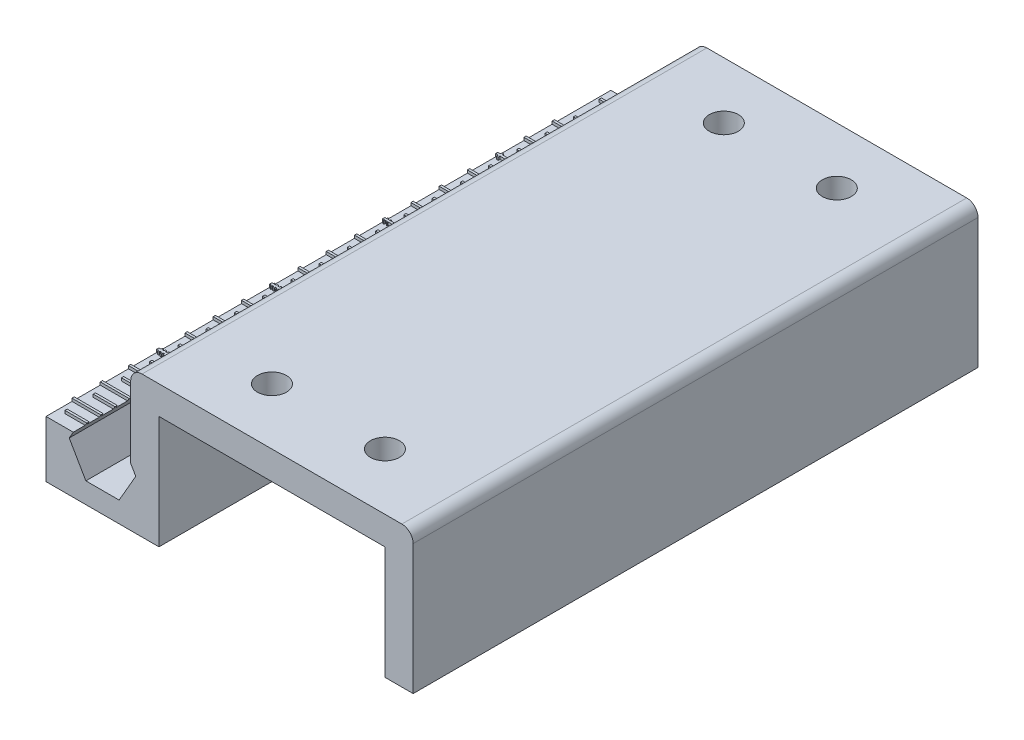
SolidWorks part; units mm, degrees
material "Printed PLA Orthotropic"
ref_plane "Front Plane" through (0, 0, 0) normal (0, 0, 1) x (1, 0, 0)
ref_plane "Top Plane" through (0, 0, 0) normal (0, 1, 0) x (1, 0, 0)
ref_plane "Right Plane" through (0, 0, 0) normal (1, 0, 0) x (0, 0, -1)
sketch "Sketch1" plane through (0, 0, 0) normal (0, 0, 1) x (1, 0, 0)
  line L0 (50.8, 0) -> (57.15, 0)
  line L2 (0, 0) -> (0, 25.4)
  line L3 (0, 25.4) -> (50.8, 25.4)
  line L4 (50.8, 0) -> (50.8, 25.4)
  line L5 (57.15, 0) -> (57.15, 29.21)
  line L6 (54.61, 31.75) -> (-3.81, 31.75)
  line L7 (0, 0) -> (-25.4, 0)
  line L14 (-25.4, 0) -> (-25.4, 12.7)
  line L15 (-6.35, 29.21) -> (-6.35, 13.068)
  line L16 (-25.4, 12.7) -> (-19.2625, 12.7)
  line L17 (-7.0908, 14.351) -> (-8.9605, 17.5895) construction
  line L18 (-12.7, 17.5895) -> (-16.4395, 17.5895) construction
  line L19 (-19.2625, 12.7) -> (-20.179, 11.1125)
  line L20 (-20.179, 11.1125) -> (-16.4395, 4.6355)
  line L21 (-16.4395, 4.6355) -> (-8.9605, 4.6355)
  line L22 (-8.9605, 4.6355) -> (-5.221, 11.1125)
  line L23 (-5.221, 11.1125) -> (-6.35, 13.068)
  line L24 (-8.9605, 17.5895) -> (-12.7, 17.5895) construction
  line L25 (-16.4395, 17.5895) -> (-18.3092, 14.351) construction
  line L26 (-18.3092, 14.351) -> (-19.2625, 12.7) construction
  line L27 (-6.35, 13.068) -> (-7.0908, 14.351) construction
  arc A0 (57.15, 29.21) -> (54.61, 31.75) centre (54.61, 29.21) ccw
  circle A1 centre (-12.7, 11.1125) radius 6.477 construction
  arc A2 (-3.81, 31.75) -> (-6.35, 29.21) centre (-3.81, 29.21) ccw
  point P10 (57.15, 31.75)
  point P12 (-6.35, 13.068)
  point P24 (-19.2625, 12.7)
  point P27 (-6.35, 31.75)
  dimension "D6" = 2.54
  dimension "D8" = 12.7
  dimension "D12" = 2.54
  dimension "D7" = 12.954
  dimension "D1" = 50.8
  dimension "D2" = 25.4
  dimension "D3" = 63.5
  dimension "D4" = 31.75
  dimension "D5" = 6.35
  dimension "D9" = 25.4
  dimension "D13" = 11.1125
  dimension "D14" = 12.7
extrude "Boss-Extrude2" add sketch "Sketch1" along normal blind 127
sketch "THE RULER" plane through (0, 0, 0) normal (0, 1, 0) x (1, 0, 0)
  line L0 (-25.4, -127) -> (-25.4, 0) construction
  line L4 (-19.2625, -6.35) -> (-19.2625, -6.858)
  line L5 (-25.4, 0) -> (0, 0) construction
  line L6 (-25.4, -6.35) -> (-25.4, -6.858)
  line L8 (-18.7306, -127) -> (-18.7306, 0) construction
  line L9 (-25.4, -12.7) -> (-18.7306, -12.7)
  line L10 (-25.4, -12.7) -> (-25.4, -13.208)
  line L11 (-25.4, -13.208) -> (-18.7306, -13.208)
  line L12 (-18.7306, -12.7) -> (-18.7306, -13.208)
  line L13 (-25.4, -19.05) -> (-18.7306, -19.05)
  line L14 (-25.4, -19.05) -> (-25.4, -19.558)
  line L15 (-25.4, -19.558) -> (-18.7306, -19.558)
  line L16 (-18.7306, -19.05) -> (-18.7306, -19.558)
  line L17 (-24.4237, -25.4) -> (-18.7306, -25.4)
  line L18 (-25.4, -25.4) -> (-24.8056, -25.4)
  line L19 (-25.4, -25.4) -> (-25.4, -25.908)
  line L20 (-25.4, -25.908) -> (-24.8056, -25.908)
  line L21 (-18.7306, -25.4) -> (-18.7306, -25.908)
  line L22 (-25.4, -32.258) -> (-18.7306, -32.258)
  line L23 (-25.4, -32.258) -> (-25.4, -31.75)
  line L24 (-25.4, -31.75) -> (-18.7306, -31.75)
  line L25 (-18.7306, -32.258) -> (-18.7306, -31.75)
  line L26 (-24.8056, -25.063) -> (-24.4237, -25.063)
  line L27 (-24.8056, -25.063) -> (-24.8056, -25.4)
  line L28 (-24.8056, -26.3147) -> (-24.4237, -26.3147)
  line L29 (-24.4237, -25.063) -> (-24.4237, -25.4)
  line L30 (-24.4237, -25.908) -> (-18.7306, -25.908)
  line L31 (-24.8056, -50.8) -> (-24.2974, -50.8)
  line L32 (-25.4, -38.1) -> (-18.7306, -38.1)
  line L33 (-25.4, -38.1) -> (-25.4, -38.608)
  line L34 (-25.4, -38.608) -> (-18.7306, -38.608)
  line L35 (-18.7306, -38.1) -> (-18.7306, -38.608)
  line L36 (-25.4, -44.45) -> (-18.7306, -44.45)
  line L37 (-25.4, -44.45) -> (-25.4, -44.958)
  line L38 (-25.4, -44.958) -> (-18.7306, -44.958)
  line L39 (-18.7306, -44.45) -> (-18.7306, -44.958)
  line L40 (-25.4, -50.8) -> (-25.0343, -50.8)
  line L41 (-25.4, -50.8) -> (-25.4, -51.308)
  line L42 (-25.4, -51.308) -> (-25.0343, -51.308)
  line L43 (-18.7306, -50.8) -> (-18.7306, -51.308)
  line L44 (-25.0343, -50.5475) -> (-24.8056, -50.5475)
  line L45 (-25.0343, -50.5475) -> (-25.0343, -50.8)
  line L46 (-25.0343, -51.584) -> (-24.8056, -51.584)
  line L47 (-24.8056, -50.5475) -> (-24.8056, -50.8)
  line L48 (-24.8056, -51.308) -> (-24.2974, -51.308)
  line L49 (-24.8056, -51.308) -> (-24.8056, -51.584)
  line L50 (-25.0343, -51.308) -> (-25.0343, -51.584)
  line L51 (-24.1534, -50.8) -> (-18.7306, -50.8)
  line L52 (-24.2974, -50.531) -> (-24.1534, -50.531)
  line L53 (-24.2974, -50.531) -> (-24.2974, -50.8)
  line L54 (-24.2974, -51.584) -> (-24.1534, -51.584)
  line L55 (-24.1534, -50.531) -> (-24.1534, -50.8)
  line L56 (-24.1534, -51.308) -> (-18.7306, -51.308)
  line L57 (-24.8056, -25.908) -> (-24.8056, -26.3147)
  line L58 (-24.4237, -25.908) -> (-24.4237, -26.3147)
  line L59 (-24.2974, -51.308) -> (-24.2974, -51.584)
  line L60 (-24.1534, -51.308) -> (-24.1534, -51.584)
  line L61 (-24.8056, -76.2) -> (-24.4237, -76.2)
  line L62 (-25.4, -57.15) -> (-18.7306, -57.15)
  line L63 (-25.4, -57.15) -> (-25.4, -57.658)
  line L64 (-25.4, -57.658) -> (-18.7306, -57.658)
  line L65 (-18.7306, -57.15) -> (-18.7306, -57.658)
  line L66 (-25.4, -63.5) -> (-18.7306, -63.5)
  line L67 (-25.4, -63.5) -> (-25.4, -64.008)
  line L68 (-25.4, -64.008) -> (-18.7306, -64.008)
  line L69 (-18.7306, -63.5) -> (-18.7306, -64.008)
  line L70 (-25.4, -69.85) -> (-18.7306, -69.85)
  line L71 (-25.4, -69.85) -> (-25.4, -70.358)
  line L72 (-25.4, -70.358) -> (-18.7306, -70.358)
  line L73 (-18.7306, -69.85) -> (-18.7306, -70.358)
  line L74 (-25.4, -76.2) -> (-25.0343, -76.2)
  line L75 (-25.4, -76.2) -> (-25.4, -76.708)
  line L76 (-25.4, -76.708) -> (-25.0343, -76.708)
  line L77 (-18.7306, -76.2) -> (-18.7306, -76.708)
  line L78 (-25.0343, -75.9757) -> (-24.8056, -75.9757)
  line L79 (-25.0343, -75.9757) -> (-25.0343, -76.2)
  line L80 (-25.0343, -76.995) -> (-24.8056, -76.995)
  line L81 (-24.8056, -75.9757) -> (-24.8056, -76.2)
  line L82 (-24.4237, -75.955) -> (-24.1534, -75.955)
  line L83 (-24.4237, -75.955) -> (-24.4237, -76.2)
  line L84 (-24.4237, -76.995) -> (-24.1534, -76.995)
  line L85 (-24.1534, -75.955) -> (-24.1534, -76.2)
  line L86 (-23.7034, -75.9188) -> (-23.4265, -75.9188)
  line L87 (-23.7034, -75.9188) -> (-23.7034, -76.2)
  line L88 (-23.7034, -76.995) -> (-23.4265, -76.995)
  line L89 (-23.4265, -75.9188) -> (-23.4265, -76.2)
  line L90 (-24.8056, -76.708) -> (-24.4237, -76.708)
  line L91 (-25.0343, -76.708) -> (-25.0343, -76.995)
  line L92 (-24.8056, -76.708) -> (-24.8056, -76.995)
  line L93 (-24.4237, -76.708) -> (-24.4237, -76.995)
  line L94 (-24.1534, -76.708) -> (-24.1534, -76.995)
  line L95 (-23.7034, -76.708) -> (-23.7034, -76.995)
  line L96 (-23.4265, -76.708) -> (-23.4265, -76.995)
  line L97 (-24.1534, -76.2) -> (-23.7034, -76.2)
  line L98 (-24.1534, -76.708) -> (-23.7034, -76.708)
  line L99 (-23.4265, -76.2) -> (-18.7306, -76.2)
  line L100 (-23.4265, -76.708) -> (-18.7306, -76.708)
  line L101 (-22.4683, -101.6) -> (-18.7306, -101.6)
  line L102 (-25.4, -82.55) -> (-18.7306, -82.55)
  line L103 (-25.4, -82.55) -> (-25.4, -83.058)
  line L104 (-25.4, -83.058) -> (-18.7306, -83.058)
  line L105 (-18.7306, -82.55) -> (-18.7306, -83.058)
  line L106 (-25.4, -89.408) -> (-18.7306, -89.408)
  line L107 (-25.4, -89.408) -> (-25.4, -88.9)
  line L108 (-25.4, -88.9) -> (-18.7306, -88.9)
  line L109 (-18.7306, -89.408) -> (-18.7306, -88.9)
  line L110 (-25.4, -95.25) -> (-18.7306, -95.25)
  line L111 (-25.4, -95.25) -> (-25.4, -95.758)
  line L112 (-25.4, -95.758) -> (-18.7306, -95.758)
  line L113 (-18.7306, -95.25) -> (-18.7306, -95.758)
  line L114 (-25.4, -101.6) -> (-24.9374, -101.6)
  line L115 (-25.4, -101.6) -> (-25.4, -102.108)
  line L116 (-25.4, -102.108) -> (-24.9374, -102.108)
  line L117 (-18.7306, -101.6) -> (-18.7306, -102.108)
  line L118 (-24.9374, -101.2815) -> (-24.6477, -101.2815)
  line L119 (-24.9374, -101.2815) -> (-24.9374, -101.6)
  line L120 (-24.9374, -102.394) -> (-24.6477, -102.394)
  line L121 (-24.6477, -101.2815) -> (-24.6477, -101.6)
  line L122 (-24.2974, -101.2815) -> (-23.9868, -101.2815)
  line L123 (-24.2974, -101.2815) -> (-24.2974, -101.6)
  line L124 (-24.2974, -102.4755) -> (-23.9868, -102.4755)
  line L125 (-23.9868, -101.2815) -> (-23.9868, -101.6)
  line L126 (-23.5885, -101.2476) -> (-23.2083, -101.2476)
  line L127 (-23.5885, -101.2476) -> (-23.5885, -101.6)
  line L128 (-23.5885, -102.4755) -> (-23.2083, -102.4755)
  line L129 (-23.2083, -101.2476) -> (-23.2083, -101.6)
  line L130 (-22.8018, -101.2646) -> (-22.4683, -101.2646)
  line L131 (-22.8018, -101.2646) -> (-22.8018, -101.6)
  line L132 (-22.8018, -102.4755) -> (-22.4683, -102.4755)
  line L133 (-22.4683, -101.2646) -> (-22.4683, -101.6)
  line L134 (-22.4683, -102.108) -> (-18.7306, -102.108)
  line L135 (-22.8018, -102.108) -> (-22.8018, -102.4755)
  line L136 (-22.4683, -102.108) -> (-22.4683, -102.4755)
  line L137 (-23.2083, -101.6) -> (-22.8018, -101.6)
  line L138 (-23.2083, -102.108) -> (-22.8018, -102.108)
  line L139 (-23.5885, -102.108) -> (-23.5885, -102.4755)
  line L140 (-23.2083, -102.108) -> (-23.2083, -102.4755)
  line L141 (-23.9868, -101.6) -> (-23.5885, -101.6)
  line L142 (-23.9868, -102.108) -> (-23.5885, -102.108)
  line L143 (-24.2974, -102.108) -> (-24.2974, -102.4755)
  line L144 (-23.9868, -102.108) -> (-23.9868, -102.4755)
  line L145 (-24.9374, -102.108) -> (-24.9374, -102.394)
  line L146 (-24.6477, -102.108) -> (-24.6477, -102.394)
  line L147 (-24.6477, -101.6) -> (-24.2974, -101.6)
  line L148 (-24.6477, -102.108) -> (-24.2974, -102.108)
  line L149 (-19.2625, -6.35) -> (-25.4, -6.35)
  line L150 (-25.4, -107.95) -> (-18.7306, -107.95)
  line L151 (-25.4, -107.95) -> (-25.4, -108.458)
  line L152 (-25.4, -108.458) -> (-18.7306, -108.458)
  line L153 (-18.7306, -107.95) -> (-18.7306, -108.458)
  line L154 (-25.4, -114.3) -> (-18.7306, -114.3)
  line L155 (-25.4, -114.3) -> (-25.4, -114.808)
  line L156 (-25.4, -114.808) -> (-18.7306, -114.808)
  line L157 (-18.7306, -114.3) -> (-18.7306, -114.808)
  line L158 (-25.4, -120.65) -> (-18.7306, -120.65)
  line L159 (-25.4, -120.65) -> (-25.4, -121.158)
  line L160 (-25.4, -121.158) -> (-18.7306, -121.158)
  line L161 (-18.7306, -120.65) -> (-18.7306, -121.158)
  line L162 (-23.8106, -47.625) -> (-18.7306, -47.625)
  line L163 (-24.3425, -3.175) -> (-19.2625, -3.175)
  line L164 (-24.3425, -3.175) -> (-24.3425, -3.683)
  line L165 (-24.3425, -3.683) -> (-19.2625, -3.683)
  line L166 (-19.2625, -3.175) -> (-19.2625, -3.683)
  line L167 (-23.8106, -9.525) -> (-18.7306, -9.525)
  line L168 (-23.8106, -9.525) -> (-23.8106, -10.033)
  line L169 (-23.8106, -10.033) -> (-18.7306, -10.033)
  line L170 (-18.7306, -9.525) -> (-18.7306, -10.033)
  line L171 (-23.8106, -15.875) -> (-18.7306, -15.875)
  line L172 (-23.8106, -15.875) -> (-23.8106, -16.383)
  line L173 (-23.8106, -16.383) -> (-18.7306, -16.383)
  line L174 (-18.7306, -15.875) -> (-18.7306, -16.383)
  line L175 (-23.8106, -22.225) -> (-18.7306, -22.225)
  line L176 (-23.8106, -22.225) -> (-23.8106, -22.733)
  line L177 (-23.8106, -22.733) -> (-18.7306, -22.733)
  line L178 (-18.7306, -22.225) -> (-18.7306, -22.733)
  line L179 (-23.8106, -28.575) -> (-18.7306, -28.575)
  line L180 (-23.8106, -28.575) -> (-23.8106, -29.083)
  line L181 (-23.8106, -29.083) -> (-18.7306, -29.083)
  line L182 (-18.7306, -28.575) -> (-18.7306, -29.083)
  line L183 (-23.8106, -34.925) -> (-18.7306, -34.925)
  line L184 (-23.8106, -34.925) -> (-23.8106, -35.433)
  line L185 (-23.8106, -35.433) -> (-18.7306, -35.433)
  line L186 (-18.7306, -34.925) -> (-18.7306, -35.433)
  line L187 (-23.8106, -41.275) -> (-18.7306, -41.275)
  line L188 (-23.8106, -41.275) -> (-23.8106, -41.783)
  line L189 (-23.8106, -41.783) -> (-18.7306, -41.783)
  line L190 (-18.7306, -41.275) -> (-18.7306, -41.783)
  line L191 (-23.8106, -47.625) -> (-23.8106, -48.133)
  line L192 (-23.8106, -48.133) -> (-18.7306, -48.133)
  line L193 (-18.7306, -47.625) -> (-18.7306, -48.133)
  line L194 (-23.8106, -53.975) -> (-18.7306, -53.975)
  line L195 (-23.8106, -53.975) -> (-23.8106, -54.483)
  line L196 (-23.8106, -54.483) -> (-18.7306, -54.483)
  line L197 (-18.7306, -53.975) -> (-18.7306, -54.483)
  line L198 (-23.8106, -60.325) -> (-18.7306, -60.325)
  line L199 (-23.8106, -60.325) -> (-23.8106, -60.833)
  line L200 (-23.8106, -60.833) -> (-18.7306, -60.833)
  line L201 (-18.7306, -60.325) -> (-18.7306, -60.833)
  line L202 (-23.8106, -66.675) -> (-18.7306, -66.675)
  line L203 (-23.8106, -66.675) -> (-23.8106, -67.183)
  line L204 (-23.8106, -67.183) -> (-18.7306, -67.183)
  line L205 (-18.7306, -66.675) -> (-18.7306, -67.183)
  line L206 (-23.8106, -73.025) -> (-18.7306, -73.025)
  line L207 (-23.8106, -73.025) -> (-23.8106, -73.533)
  line L208 (-23.8106, -73.533) -> (-18.7306, -73.533)
  line L209 (-18.7306, -73.025) -> (-18.7306, -73.533)
  line L210 (-23.8106, -79.375) -> (-18.7306, -79.375)
  line L211 (-23.8106, -79.375) -> (-23.8106, -79.883)
  line L212 (-23.8106, -79.883) -> (-18.7306, -79.883)
  line L213 (-18.7306, -79.375) -> (-18.7306, -79.883)
  line L214 (-23.8106, -85.725) -> (-18.7306, -85.725)
  line L215 (-23.8106, -85.725) -> (-23.8106, -86.233)
  line L216 (-23.8106, -86.233) -> (-18.7306, -86.233)
  line L217 (-18.7306, -85.725) -> (-18.7306, -86.233)
  line L218 (-23.8106, -92.075) -> (-18.7306, -92.075)
  line L219 (-23.8106, -92.075) -> (-23.8106, -92.583)
  line L220 (-23.8106, -92.583) -> (-18.7306, -92.583)
  line L221 (-18.7306, -92.075) -> (-18.7306, -92.583)
  line L222 (-23.8106, -98.425) -> (-18.7306, -98.425)
  line L223 (-23.8106, -98.425) -> (-23.8106, -98.933)
  line L224 (-23.8106, -98.933) -> (-18.7306, -98.933)
  line L225 (-18.7306, -98.425) -> (-18.7306, -98.933)
  line L226 (-23.8106, -104.775) -> (-18.7306, -104.775)
  line L227 (-23.8106, -104.775) -> (-23.8106, -105.283)
  line L228 (-23.8106, -105.283) -> (-18.7306, -105.283)
  line L229 (-18.7306, -104.775) -> (-18.7306, -105.283)
  line L230 (-23.8106, -111.125) -> (-18.7306, -111.125)
  line L231 (-23.8106, -111.125) -> (-23.8106, -111.633)
  line L232 (-23.8106, -111.633) -> (-18.7306, -111.633)
  line L233 (-18.7306, -111.125) -> (-18.7306, -111.633)
  line L234 (-23.8106, -117.475) -> (-18.7306, -117.475)
  line L235 (-23.8106, -117.475) -> (-23.8106, -117.983)
  line L236 (-23.8106, -117.983) -> (-18.7306, -117.983)
  line L237 (-18.7306, -117.475) -> (-18.7306, -117.983)
  line L238 (-23.8106, -123.825) -> (-18.7306, -123.825)
  line L239 (-23.8106, -123.825) -> (-23.8106, -124.333)
  line L240 (-23.8106, -124.333) -> (-18.7306, -124.333)
  line L241 (-18.7306, -123.825) -> (-18.7306, -124.333)
  line L242 (-19.2625, -6.858) -> (-25.4, -6.858)
  line L243 (-19.2625, -127) -> (-19.2625, 0) construction
  point P8 (0, 0)
  point P9 (0, 0)
  point P216 (-23.9284, -76.2)
  point P245 (0, 0)
  point P246 (0, 0)
  dimension "D2" = 0.508
  dimension "D3" = 6.35
  dimension "D4" = 0.508
  dimension "D5" = 6.35
  dimension "D6" = 6.35
  dimension "D7" = 0.508
  dimension "D8" = 0.508
  dimension "D9" = 6.35
  dimension "D10" = 0.508
  dimension "D11" = 6.35
  dimension "D12" = 0.508
  dimension "D13" = 6.35
  dimension "D14" = 0.508
  dimension "D15" = 6.35
  dimension "D16" = 0.508
  dimension "D17" = 6.35
  dimension "D18" = 0.508
  dimension "D19" = 6.35
  dimension "D20" = 0.508
  dimension "D21" = 6.35
  dimension "D22" = 0.508
  dimension "D23" = 6.35
  dimension "D24" = 0.508
  dimension "D25" = 6.35
  dimension "D26" = 0.508
  dimension "D27" = 6.35
  dimension "D28" = 0.508
  dimension "D29" = 6.35
  dimension "D30" = 0.508
  dimension "D31" = 6.35
  dimension "D32" = 0.508
  dimension "D33" = 6.35
  dimension "D34" = 0.508
  dimension "D35" = 6.35
  dimension "D36" = 0.508
  dimension "D37" = 6.35
  dimension "D38" = 0.508
  dimension "D39" = 6.35
  dimension "D40" = 5.08
  dimension "D41" = 0.508
  dimension "D42" = 3.175
  dimension "D43" = 5.08
  dimension "D44" = 0.508
  dimension "D45" = 5.08
  dimension "D46" = 3.175
  dimension "D47" = 0.508
  dimension "D48" = 5.08
  dimension "D49" = 3.175
  dimension "D50" = 0.508
  dimension "D51" = 5.08
  dimension "D52" = 3.175
  dimension "D53" = 0.508
  dimension "D54" = 3.175
  dimension "D55" = 5.08
  dimension "D56" = 0.508
  dimension "D57" = 3.175
  dimension "D58" = 5.08
  dimension "D59" = 0.508
  dimension "D60" = 3.175
  dimension "D61" = 0.508
  dimension "D62" = 5.08
  dimension "D63" = 3.175
  dimension "D64" = 0.508
  dimension "D65" = 3.175
  dimension "D66" = 0.508
  dimension "D67" = 5.08
  dimension "D68" = 5.08
  dimension "D69" = 3.175
  dimension "D70" = 5.08
  dimension "D71" = 0.508
  dimension "D72" = 5.08
  dimension "D73" = 3.175
  dimension "D74" = 0.508
  dimension "D75" = 5.08
  dimension "D76" = 3.175
  dimension "D77" = 0.508
  dimension "D78" = 5.08
  dimension "D79" = 3.175
  dimension "D80" = 0.508
  dimension "D81" = 3.175
  dimension "D82" = 5.08
  dimension "D83" = 0.508
  dimension "D84" = 5.08
  dimension "D85" = 3.175
  dimension "D86" = 0.508
  dimension "D87" = 5.08
  dimension "D88" = 3.175
  dimension "D89" = 0.508
  dimension "D90" = 5.08
  dimension "D91" = 3.175
  dimension "D92" = 0.508
  dimension "D93" = 5.08
  dimension "D94" = 3.175
  dimension "D95" = 0.508
  dimension "D96" = 5.08
  dimension "D97" = 3.175
  dimension "D98" = 0.508
  dimension "D99" = 3.175
extrude "Boss-Extrude6" add sketch "THE RULER" along normal blind 13.335 contours L12 L9 L10 L11 | L186 L183 L184 L185 | L60 L56 L43 L51 L55 L52 L53 L31 L47 L44 L45 L40 L41 L42 L50 L46 L49 L48 L59 L54 | L197 L194 L195 L196 | L65 L62 L63 L64 | L69 L66 L67 L68 | L73 L70 L71 L72 | L96 L100 L77 L99 L89 L86 L87 L97 L85 L82 L83 L61 L81 L78 L79 L74 L75 L76 L91 L80 L92 L90 L93 L84 L94 L98 L95 L88 | L225 L222 L223 L224 | L113 L110 L111 L112 | L221 L218 L219 L220 | L106 L109 L108 L107 | L217 L214 L215 L216 | L105 L102 L103 L104 | L213 L210 L211 L212 | L146 L148 L143 L124 L144 L142 L139 L128 L140 L138 L135 L132 L136 L134 L117 L101 L133 L130 L131 L137 L129 L126 L127 L141 L125 L122 L123 L147 L121 L118 L119 L114 L115 L116 L145 L120 | L229 L226 L227 L228 | L153 L150 L151 L152 | L233 L230 L231 L232 | L157 L154 L155 L156 | L237 L234 L235 L236 | L241 L238 L239 L240 | L161 L158 L159 L160 | L165 L166 L163 L164 | L169 L170 L167 L168 | L173 L174 L171 L172 | L15 L16 L13 L14 | L177 L178 L175 L176 | L17 L21 L30 L58 L28 L57 L20 L19 L18 L27 L26 L29 | L181 L182 L179 L180 | L24 L25 L22 L23 | L34 L35 L32 L33 | L189 L190 L187 L188 | L36 L39 L38 L37 | L162 L193 L192 L191 | L200 L201 L198 L199 | L204 L205 L202 L203 | L206 L209 L208 L207
sketch "Sketch9" plane through (0, 0, 127) normal (0, 0, 1) x (1, 0, 0)
  line L0 (-8.9605, 4.6355) -> (-16.4395, 4.6355) construction
  line L7 (-8.9605, 17.5895) -> (-16.4395, 17.5895)
  line L8 (-16.4395, 17.5895) -> (-20.179, 11.1125)
  line L9 (-20.179, 11.1125) -> (-16.4395, 4.6355)
  line L10 (-16.4395, 4.6355) -> (-8.9605, 4.6355)
  line L11 (-8.9605, 4.6355) -> (-5.221, 11.1125)
  line L12 (-5.221, 11.1125) -> (-8.9605, 17.5895)
  line L13 (-16.4395, 4.6355) -> (-20.179, 11.1125) construction
  line L14 (-5.221, 11.1125) -> (-8.9605, 4.6355) construction
  circle A0 centre (-12.7, 11.1125) radius 6.477 construction
extrude "Cut-Extrude1" cut sketch "Sketch9" against normal blind 127
sketch "Sketch10" plane through (0, 31.75, 0) normal (0, 1, 0) x (1, 0, 0)
  line L0 (0, -63.5) -> (50.8, -63.5) construction
  line L4 (50.8, 0) -> (0, 0)
  line L5 (50.8, -127) -> (50.8, 0)
  line L6 (0, -127) -> (50.8, -127)
  line L7 (0, 0) -> (0, -127)
  line L8 (50.8, 0) -> (0, 0) construction
  line L9 (50.8, -127) -> (50.8, 0) construction
  line L10 (0, -127) -> (50.8, -127) construction
  line L11 (0, 0) -> (0, -127) construction
  circle A0 centre (12.7, -12.7) radius 3.2639
  circle A1 centre (38.1, -12.7) radius 3.2639
  circle A2 centre (38.1, -114.3) radius 3.2639
  circle A3 centre (12.7, -114.3) radius 3.2639
  dimension "D2" = 12.7
  dimension "D3" = 12.7
  dimension "D4" = 6.5278
  dimension "D5" = 6.5278
  dimension "D6" = 12.7
  dimension "D7" = 12.7
  dimension "D1" = 0
extrude "Cut-Extrude2" cut sketch "Sketch10" against normal through all
